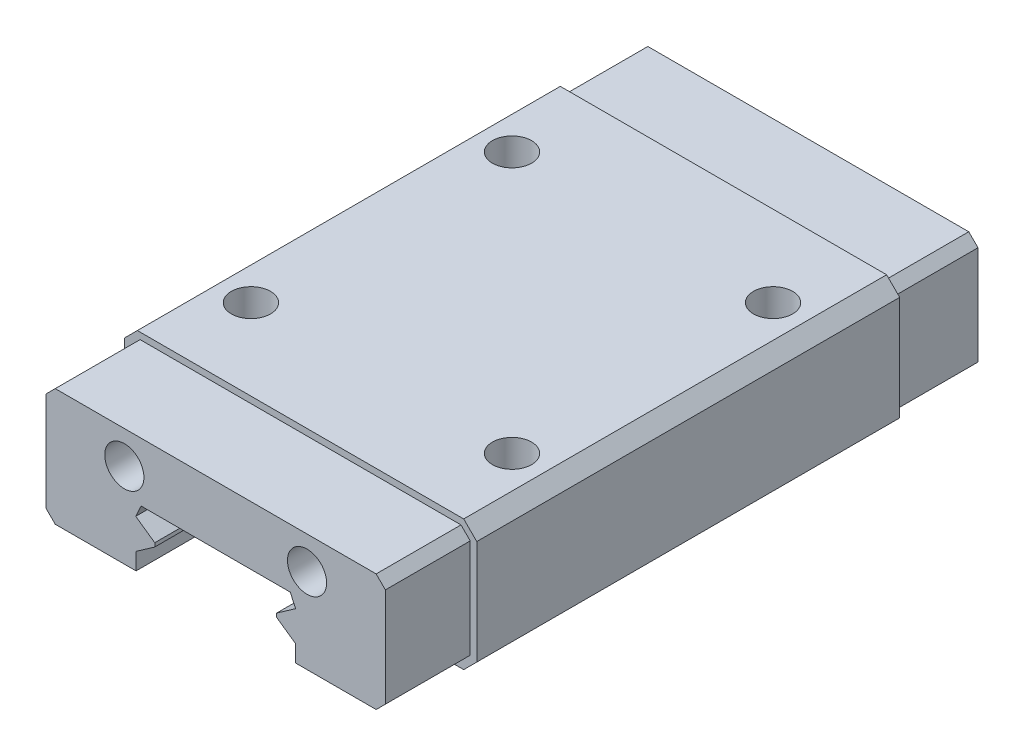
SolidWorks part; units mm, degrees
ref_plane "前视基准面" through (0, 0, 0) normal (0, 0, 1) x (1, 0, 0)
ref_plane "上视基准面" through (0, 0, 0) normal (0, 1, 0) x (1, 0, 0)
ref_plane "右视基准面" through (0, 0, 0) normal (1, 0, 0) x (0, 0, -1)
sketch "草图1" plane through (0, 0, 0) normal (0, 0, 1) x (1, 0, 0)
  line L0 (-15.0559, 17.4767) -> (-3.7613, 17.4767) construction
  line L1 (-3.7613, 17.4767) -> (-3.4086, 16.7202) construction
  line L2 (-3.4086, 16.7202) -> (-4.8404, 15.7177) construction
  line L3 (-4.8404, 15.7177) -> (-4.8404, 15.3269) construction
  line L4 (-4.8404, 15.3269) -> (-3.4086, 14.3244) construction
  line L5 (-3.4086, 14.3244) -> (-3.4086, 9.4767) construction
  line L6 (-3.4086, 9.4767) -> (-15.4086, 9.4767) construction
  line L7 (-15.4086, 9.4767) -> (-15.4086, 14.3244) construction
  line L8 (-15.4086, 14.3244) -> (-13.9768, 15.3269) construction
  line L9 (-13.9768, 15.3269) -> (-13.9768, 15.7177) construction
  line L10 (-13.9768, 15.7177) -> (-15.4086, 16.7202) construction
  line L11 (-15.4086, 16.7202) -> (-15.0559, 17.4767) construction
  line L12 (-15.1196, 17.5767) -> (-3.6976, 17.5767)
  line L13 (-3.6976, 17.5767) -> (-3.2825, 16.6865)
  line L14 (-3.2825, 16.6865) -> (-4.7404, 15.6656)
  line L15 (-4.7404, 15.6656) -> (-4.7404, 15.379)
  line L16 (-4.7404, 15.379) -> (-3.3086, 14.3764)
  line L17 (-3.3086, 14.3764) -> (-3.3086, 12.5767)
  line L19 (-15.5086, 12.5767) -> (-15.5086, 14.3764)
  line L20 (-15.5086, 14.3764) -> (-14.0768, 15.379)
  line L21 (-14.0768, 15.379) -> (-14.0768, 15.6656)
  line L22 (-14.0768, 15.6656) -> (-15.5347, 16.6865)
  line L23 (-15.5347, 16.6865) -> (-15.1196, 17.5767)
  line L24 (-21.9086, 22.5767) -> (3.0914, 22.5767)
  line L25 (-22.9086, 21.5767) -> (-22.9086, 13.5767)
  line L26 (-21.9086, 12.5767) -> (-15.5086, 12.5767)
  line L27 (4.0914, 21.5767) -> (4.0914, 13.5767)
  line L28 (3.0914, 12.5767) -> (-3.3086, 12.5767)
  line L29 (-22.9086, 13.5767) -> (-21.9086, 12.5767)
  line L30 (-22.9086, 21.5767) -> (-21.9086, 22.5767)
  line L31 (4.0914, 13.5767) -> (3.0914, 12.5767)
  line L32 (3.0914, 22.5767) -> (4.0914, 21.5767)
  point P17 (-22.9086, 22.5767)
  point P25 (4.0914, 22.5767)
  point P26 (-9.4086, 17.5767)
  point P27 (-9.4086, 22.5767)
  point P29 (-22.9086, 12.5767)
  point P30 (4.0914, 12.5767)
  dimension "D1" = 125
  dimension "D2" = 125
  dimension "D3" = 100
  dimension "D4" = 100
  dimension "D5" = 125
  dimension "D6" = 8
  dimension "D7" = 12
  dimension "D8" = 0.1
  dimension "D9" = 0.1
  dimension "D10" = 0.1
  dimension "D11" = 0.1
  dimension "D12" = 0.1
  dimension "D13" = 0.1
  dimension "D14" = 0.1
  dimension "D15" = 0.1
  dimension "D16" = 0.1
  dimension "D17" = 0.1
  dimension "D18" = 0.1
  dimension "D19" = 27
  dimension "D20" = 5
  dimension "D21" = 10
  dimension "D22" = 7.4
  dimension "D23" = 10
extrude "凸台-拉伸1" add sketch "草图1" along normal blind 45.4
sketch "草图2" plane through (0, 22.5767, 0) normal (0, 1, 0) x (1, 0, 0)
  line L0 (3.0914, -45.4) -> (3.0914, 0) construction
  line L1 (-21.9086, -45.4) -> (-21.9086, 0) construction
  line L2 (3.0914, 0) -> (-21.9086, 0) construction
  line L3 (-23.9086, -6.5) -> (5.0914, -6.5) construction
  line L4 (-23.9086, -6.5) -> (-23.9086, -38.9) construction
  line L5 (-23.9086, -38.9) -> (5.0914, -38.9) construction
  line L6 (5.0914, -6.5) -> (5.0914, -38.9) construction
  line L7 (-21.9086, 0) -> (-21.9086, -6.5)
  line L8 (-21.9086, -6.5) -> (3.0914, -6.5)
  line L9 (3.0914, -6.5) -> (3.0914, 0)
  line L10 (3.0914, 0) -> (-21.9086, 0)
  point P0 (3.0914, -22.7)
  point P1 (-21.9086, -22.7)
  point P10 (5.0914, -22.7)
  point P11 (-23.9086, -22.7)
  point P12 (-9.4086, 0)
  point P13 (-9.4086, -6.5)
  dimension "D1" = 32.4
  dimension "D2" = 29
extrude "切除-拉伸1" cut sketch "草图2" against normal blind 0.5
sketch "草图3" plane through (-22.2426, 22.2426, 0) normal (-0.7071, 0.7071, 0) x (0, 0, 1)
  line L0 (6.5, 0.4724) -> (6.5, -0.9418)
  line L1 (45.4, -0.9418) -> (0, -0.9418) construction
  line L2 (6.5, -0.9418) -> (0, -0.9418)
  line L3 (0, -0.9418) -> (0, 0.4724)
  line L4 (0, 0.4724) -> (6.5, 0.4724)
extrude "切除-拉伸2" cut sketch "草图3" against normal blind 0.5
sketch "草图4" plane through (-22.9086, 0, 0) normal (-1, 0, 0) x (0, 0, 1)
  line L0 (6.5, 21.5767) -> (6.5, 13.5767)
  line L1 (45.4, 13.5767) -> (0, 13.5767) construction
  line L2 (6.5, 13.5767) -> (0, 13.5767)
  line L3 (0, 13.5767) -> (0, 21.5767)
  line L4 (0, 21.5767) -> (6.5, 21.5767)
extrude "切除-拉伸3" cut sketch "草图4" against normal blind 0.5
sketch "草图5" plane through (-4.6659, -4.6659, 0) normal (-0.7071, -0.7071, 0) x (0, 0, 1)
  line L0 (6.5, 25.799) -> (6.5, 24.3848)
  line L1 (45.4, 24.3848) -> (0, 24.3848) construction
  line L2 (6.5, 24.3848) -> (0, 24.3848)
  line L3 (0, 24.3848) -> (0, 25.799)
  line L4 (0, 30.9558) -> (0, 25.4454) construction
  line L5 (0, 25.799) -> (6.5, 25.799) construction
  line L6 (0, 25.799) -> (6.5, 25.799)
extrude "切除-拉伸4" cut sketch "草图5" against normal blind 0.5
sketch "草图6" plane through (0, 12.5767, 0) normal (0, -1, 0) x (1, 0, 0)
  line L7 (-21.9086, 6.5) -> (-15.5086, 6.5)
  line L8 (-21.9086, 6.5) -> (-21.9086, 0)
  line L9 (-21.9086, 0) -> (-15.5086, 0)
  line L10 (-15.5086, 6.5) -> (-15.5086, 0)
extrude "切除-拉伸5" cut sketch "草图6" against normal blind 0.5
sketch "草图7" plane through (12.8341, 12.8341, 0) normal (0.7071, 0.7071, 0) x (0, 0, -1)
  line L1 (-6.5, 13.7782) -> (0, 13.7782)
  line L2 (-6.5, 13.7782) -> (-6.5, 12.364)
  line L3 (-6.5, 12.364) -> (0, 12.364)
  line L4 (0, 13.7782) -> (0, 12.364)
extrude "切除-拉伸6" cut sketch "草图7" against normal blind 0.5
sketch "草图8" plane through (4.0914, 0, 0) normal (1, 0, 0) x (0, 0, -1)
  line L1 (-6.5, 21.5767) -> (0, 21.5767)
  line L2 (-6.5, 21.5767) -> (-6.5, 13.5767)
  line L3 (-6.5, 13.5767) -> (0, 13.5767)
  line L4 (0, 21.5767) -> (0, 13.5767)
extrude "切除-拉伸7" cut sketch "草图8" against normal blind 0.5
sketch "草图9" plane through (-4.7426, 4.7426, 0) normal (0.7071, -0.7071, 0) x (0, 0, -1)
  line L1 (-6.5, 12.4932) -> (0, 12.4932)
  line L2 (-6.5, 12.4932) -> (-6.5, 11.079)
  line L3 (-6.5, 11.079) -> (0, 11.079)
  line L4 (0, 12.4932) -> (0, 11.079)
extrude "切除-拉伸8" cut sketch "草图9" against normal blind 0.5
sketch "草图10" plane through (0, 12.5767, 0) normal (0, -1, 0) x (1, 0, 0)
  line L1 (3.0914, 6.5) -> (-3.3086, 6.5)
  line L2 (3.0914, 6.5) -> (3.0914, 0)
  line L3 (3.0914, 0) -> (-3.3086, 0)
  line L4 (-3.3086, 6.5) -> (-3.3086, 0)
extrude "切除-拉伸9" cut sketch "草图10" against normal blind 0.5
sketch "草图11" plane through (0, 22.5767, 0) normal (0, 1, 0) x (1, 0, 0)
  line L0 (3.0914, -45.4) -> (3.0914, -6.5) construction
  line L1 (-21.9086, -45.4) -> (3.0914, -45.4)
  line L2 (-21.9086, -45.4) -> (-21.9086, -38.9)
  line L3 (-21.9086, -38.9) -> (3.0914, -38.9)
  line L4 (3.0914, -45.4) -> (3.0914, -38.9)
  dimension "D1" = 6.5
extrude "切除-拉伸10" cut sketch "草图11" against normal blind 0.5
sketch "草图12" plane through (12.8341, 12.8341, 0) normal (0.7071, 0.7071, 0) x (0, 0, -1)
  line L1 (-38.9, 13.7782) -> (-45.4, 13.7782)
  line L2 (-38.9, 13.7782) -> (-38.9, 12.364)
  line L3 (-38.9, 12.364) -> (-45.4, 12.364)
  line L4 (-45.4, 13.7782) -> (-45.4, 12.364)
extrude "切除-拉伸11" cut sketch "草图12" against normal blind 0.5
sketch "草图13" plane through (4.0914, 0, 0) normal (1, 0, 0) x (0, 0, -1)
  line L1 (-38.9, 21.5767) -> (-45.4, 21.5767)
  line L2 (-38.9, 21.5767) -> (-38.9, 13.5767)
  line L3 (-38.9, 13.5767) -> (-45.4, 13.5767)
  line L4 (-45.4, 21.5767) -> (-45.4, 13.5767)
extrude "切除-拉伸12" cut sketch "草图13" against normal blind 0.5
sketch "草图14" plane through (-4.7426, 4.7426, 0) normal (0.7071, -0.7071, 0) x (0, 0, -1)
  line L1 (-38.9, 12.4932) -> (-45.4, 12.4932)
  line L2 (-38.9, 12.4932) -> (-38.9, 11.079)
  line L3 (-38.9, 11.079) -> (-45.4, 11.079)
  line L4 (-45.4, 12.4932) -> (-45.4, 11.079)
extrude "切除-拉伸13" cut sketch "草图14" against normal blind 0.5
sketch "草图15" plane through (0, 12.5767, 0) normal (0, -1, 0) x (1, 0, 0)
  line L1 (3.0914, 38.9) -> (-3.3086, 38.9)
  line L2 (3.0914, 38.9) -> (3.0914, 45.4)
  line L3 (3.0914, 45.4) -> (-3.3086, 45.4)
  line L4 (-3.3086, 38.9) -> (-3.3086, 45.4)
extrude "切除-拉伸14" cut sketch "草图15" against normal blind 0.5
sketch "草图16" plane through (-22.2426, 22.2426, 0) normal (-0.7071, 0.7071, 0) x (0, 0, 1)
  line L1 (38.9, 0.4724) -> (45.4, 0.4724)
  line L2 (38.9, 0.4724) -> (38.9, -0.9418)
  line L3 (38.9, -0.9418) -> (45.4, -0.9418)
  line L4 (45.4, 0.4724) -> (45.4, -0.9418)
extrude "切除-拉伸15" cut sketch "草图16" against normal blind 0.5
sketch "草图17" plane through (-22.9086, 0, 0) normal (-1, 0, 0) x (0, 0, 1)
  line L1 (38.9, 21.5767) -> (45.4, 21.5767)
  line L2 (38.9, 21.5767) -> (38.9, 13.5767)
  line L3 (38.9, 13.5767) -> (45.4, 13.5767)
  line L4 (45.4, 21.5767) -> (45.4, 13.5767)
extrude "切除-拉伸16" cut sketch "草图17" against normal blind 0.5
sketch "草图18" plane through (-4.6659, -4.6659, 0) normal (-0.7071, -0.7071, 0) x (0, 0, 1)
  line L1 (38.9, 25.799) -> (45.4, 25.799)
  line L2 (38.9, 25.799) -> (38.9, 24.3848)
  line L3 (38.9, 24.3848) -> (45.4, 24.3848)
  line L4 (45.4, 25.799) -> (45.4, 24.3848)
extrude "切除-拉伸17" cut sketch "草图18" against normal blind 0.5
sketch "草图19" plane through (0, 12.5767, 0) normal (0, -1, 0) x (1, 0, 0)
  line L0 (-15.5086, 45.4) -> (-15.5086, 0) construction
  line L1 (-21.9086, 45.4) -> (-15.5086, 45.4)
  line L2 (-21.9086, 45.4) -> (-21.9086, 38.9)
  line L3 (-21.9086, 38.9) -> (-15.5086, 38.9)
  line L4 (-15.5086, 45.4) -> (-15.5086, 38.9)
extrude "切除-拉伸18" cut sketch "草图19" against normal blind 0.5
sketch "草图20" plane through (0, 22.5767, 0) normal (0, 1, 0) x (1, 0, 0)
  line L0 (-21.9086, -38.9) -> (-21.9086, -6.5) construction
  line L1 (-19.4086, -12.7) -> (0.5914, -12.7) construction
  line L2 (-19.4086, -12.7) -> (-19.4086, -32.7) construction
  line L3 (-19.4086, -32.7) -> (0.5914, -32.7) construction
  line L4 (0.5914, -12.7) -> (0.5914, -32.7) construction
  line L5 (-21.9086, -6.5) -> (3.0914, -6.5) construction
  circle A0 centre (-19.4086, -12.7) radius 1.5
  circle A1 centre (0.5914, -12.7) radius 1.5
  circle A2 centre (0.5914, -32.7) radius 1.5
  circle A3 centre (-19.4086, -32.7) radius 1.5
  point P4 (-19.4086, -22.7)
  point P5 (-21.9086, -22.7)
  point P6 (-9.4086, -12.7)
  point P9 (-9.4086, -6.5)
  dimension "D1" = 20
  dimension "D2" = 20
extrude "切除-拉伸19" cut sketch "草图20" against normal blind 3.5
sketch "草图21" plane through (0, 0, 45.4) normal (0, 0, 1) x (1, 0, 0)
  line L0 (-22.4086, 13.7838) -> (-22.4086, 21.3696) construction
  line L1 (3.5914, 21.3696) -> (3.5914, 13.7838) construction
  line L2 (2.8843, 22.0767) -> (-21.7015, 22.0767) construction
  circle A0 centre (-16.4086, 19.5767) radius 1.5
  circle A1 centre (-2.4086, 19.5767) radius 1.5
  dimension "D1" = 6
  dimension "D2" = 6
  dimension "D3" = 2.5
  dimension "D4" = 2.5
extrude "切除-拉伸21" cut sketch "草图21" against normal blind 3.5
sketch "草图22" plane through (0, 0, 0) normal (0, 0, -1) x (-1, 0, 0)
  line L0 (-3.5914, 21.3696) -> (-3.5914, 13.7838) construction
  line L3 (-2.8843, 22.0767) -> (21.7015, 22.0767) construction
  line L8 (22.4086, 13.7838) -> (22.4086, 21.3696) construction
  line L10 (21.7015, 22.0767) -> (-2.8843, 22.0767) construction
  circle A0 centre (2.4086, 19.5767) radius 1.5
  circle A1 centre (16.4086, 19.5767) radius 1.5
  point P6 (0, 0)
  point P7 (0, 0)
  point P8 (1.724, 22.0767)
  point P9 (-5.2641, 22.0364)
  point P16 (16.7278, 22.0767)
  dimension "D1" = 6
  dimension "D2" = 2.5
  dimension "D3" = 6
  dimension "D4" = 2.5
extrude "切除-拉伸22" cut sketch "草图22" against normal blind 3.5
